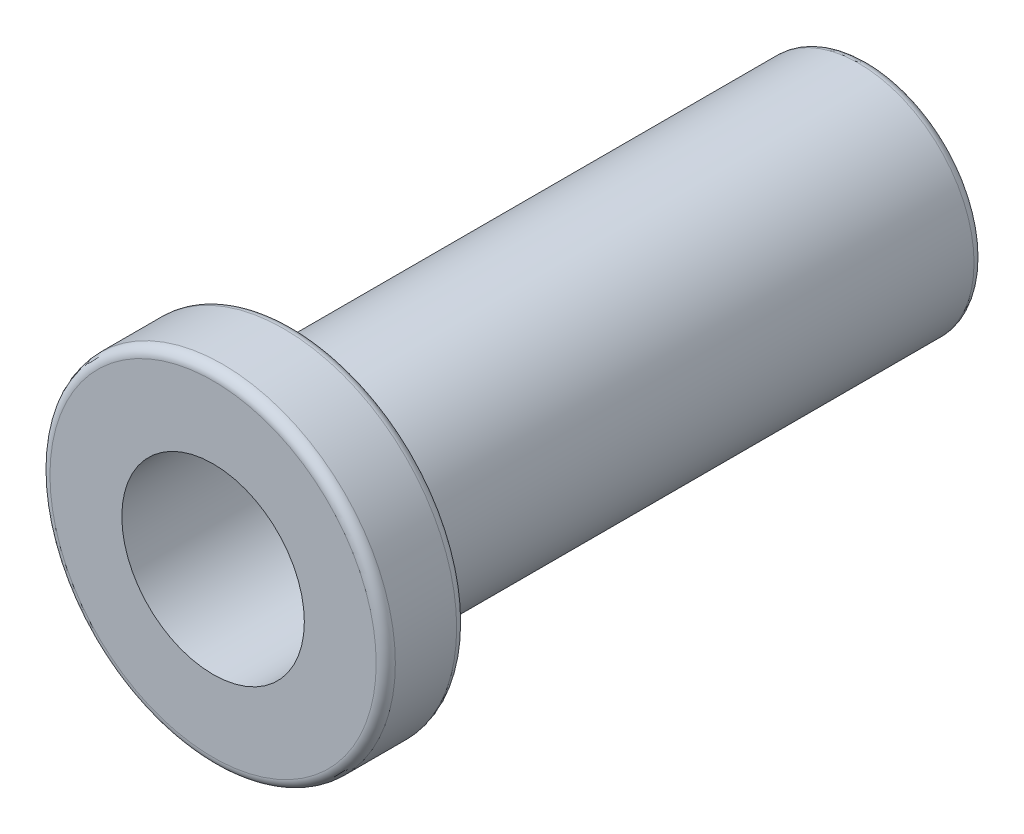
SolidWorks part; units mm, degrees
ref_plane "Plano frontal" through (0, 0, 0) normal (0, 0, 1) x (1, 0, 0)
ref_plane "Plano superior" through (0, 0, 0) normal (0, 1, 0) x (1, 0, 0)
ref_plane "Plano direito" through (0, 0, 0) normal (1, 0, 0) x (0, 0, -1)
sketch "Esboço1" plane through (0, 0, -0.4046) normal (0, 0, 1) x (1, 0, 0)
  circle A1 centre (70.7953, 51.2583) radius 4.7625
  circle A2 centre (70.7953, 51.2583) radius 6.0125
  dimension "D1" = 12.025
  dimension "D2" = 9.525
extrude "Ressalto-extrusão1" add sketch "Esboço1" along normal blind 4.2 and the other way blind 30
sketch "Esboço2" plane through (0, 0, -0.4046) normal (0, 0, 1) x (1, 0, 0)
  circle A0 centre (70.7953, 51.2583) radius 6.0125
  circle A1 centre (70.7953, 51.2583) radius 9.0125
  dimension "D1" = 18.025
  dimension "D2" = 12.025
extrude "Ressalto-extrusão2" add sketch "Esboço2" along normal blind 4.2
fillet "Filete2" radius 0.5 3 edges at (79.8078, 51.2583, -0.4046) (76.8078, 51.2583, -30.4046) (79.8078, 51.2583, 3.7954)
equation "\"D2@Esboço1\" =\"D_Barra@Inversor3.SLDASM\""
equation "\"D2@Esboço2\"=\"H_Barra@Inversor3.SLDASM\""
equation "\"D1@Esboço1\" = \"H_Barra@Inversor3.SLDASM\""
equation "\"D1@Esboço2\"=\"D2@Esboço2\"+6"
